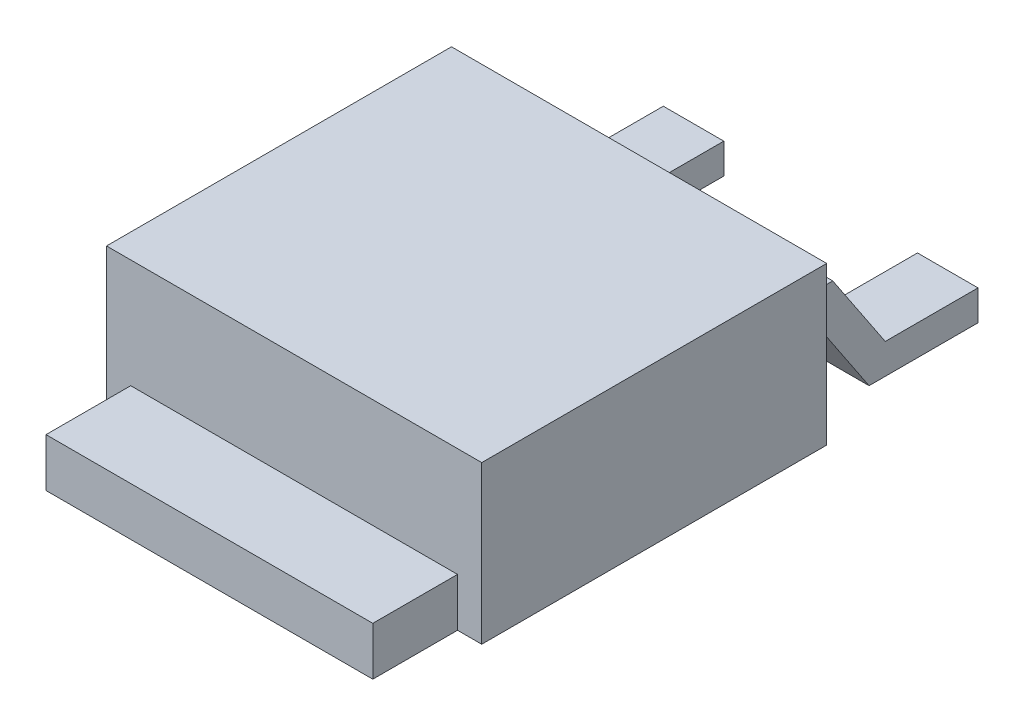
SolidWorks part; units mm, degrees
ref_plane "Alzado" through (0, 0, 0) normal (0, 0, 1) x (1, 0, 0)
ref_plane "Planta" through (0, 0, 0) normal (0, 1, 0) x (1, 0, 0)
ref_plane "Vista lateral" through (0, 0, 0) normal (1, 0, 0) x (0, 0, -1)
sketch "Croquis1" plane through (0, 0, 0) normal (1, 0, 0) x (0, 0, -1)
  line L1 (0, 0) -> (5.7, 0)
  line L2 (0, 0) -> (0, 2.6)
  line L3 (0, 2.6) -> (5.7, 2.6)
  line L4 (5.7, 0) -> (5.7, 2.6)
  dimension "D1" = 5.7
  dimension "D2" = 2.6
extrude "Saliente-Extruir1" add sketch "Croquis1" along normal blind 6.2
sketch "Croquis2" plane through (0, 0, 0) normal (0, 0, 1) x (1, 0, 0)
  line L0 (6.2, 0) -> (0, 0) construction
  line L1 (0.4, 0) -> (5.8, 0)
  line L2 (0.4, 0) -> (0.4, 0.8)
  line L3 (0.4, 0.8) -> (5.8, 0.8)
  line L4 (5.8, 0) -> (5.8, 0.8)
  line L7 (0.4, 0.8) -> (0, 0.8) construction
  line L8 (0, 2.6) -> (0, 0) construction
  line L9 (5.8, 0.8) -> (6.2, 0.8) construction
  line L10 (6.2, 2.6) -> (6.2, 0) construction
  dimension "D1" = 0.8
  dimension "D2" = 5.4
extrude "Saliente-Extruir2" add sketch "Croquis2" along normal blind 1.4
ref_plane "Plano1" through (0.5, 0, 0) normal (-1, 0, 0) x (0, 0, 1)
sketch "Croquis3" plane through (0.5, 0, 0) normal (-1, 0, 0) x (0, 0, 1)
  line L0 (-5.7, 1.8) -> (-6.3, 1.8)
  line L1 (-5.7, 0) -> (-5.7, 2.6) construction
  line L2 (-6.3, 1.8) -> (-7.1675, 0.5)
  line L3 (-7.1675, 0.5) -> (-8.7, 0.5)
  line L4 (-8.7, 0.5) -> (-8.7, 0)
  line L5 (-8.7, 0) -> (-6.9, 0)
  line L6 (-6.9, 0) -> (-6.0325, 1.3)
  line L7 (-6.0325, 1.3) -> (-5.7, 1.3)
  line L8 (-5.7, 1.3) -> (-5.7, 1.8)
  line L9 (-5.7, 0) -> (-7.6999, 0) construction
  dimension "D1" = 3
  dimension "D2" = 1.2
  dimension "D3" = 0.5
  dimension "D4" = 0.8
  dimension "D5" = 0.6
  dimension "D6" = 0.5
  dimension "D7" = 0.5
extrude "Saliente-Extruir3" add sketch "Croquis3" against normal blind 1
pattern_linear "MatrizL1" count 2 spacing 4.2 along (1, 0, 0) of "Saliente-Extruir3"
